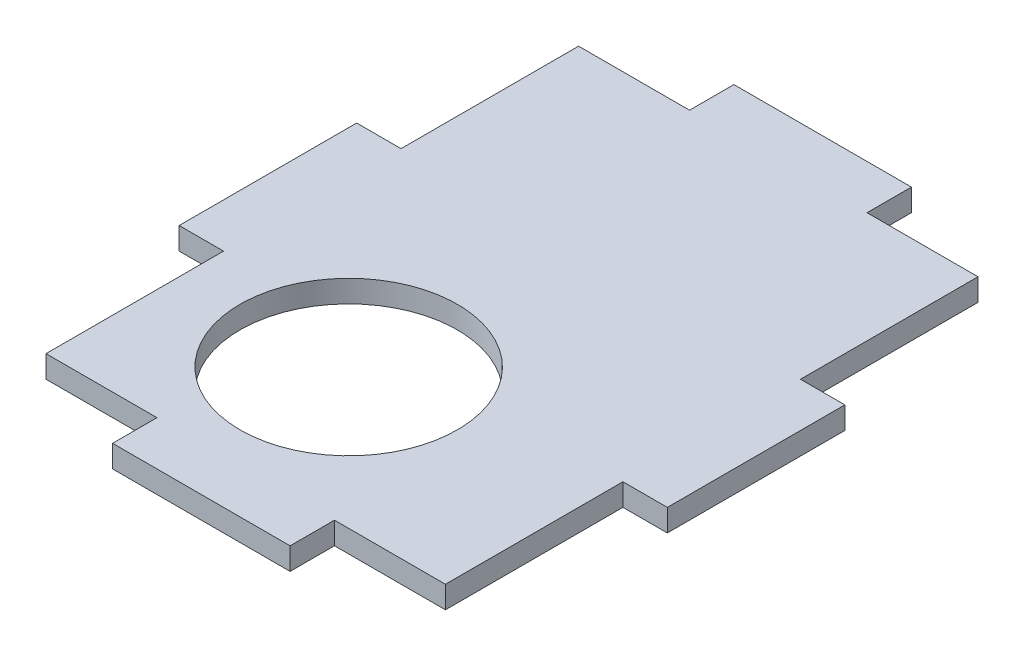
SolidWorks part; units mm, degrees
ref_plane "Front Plane" through (0, 0, 0) normal (0, 0, 1) x (1, 0, 0)
ref_plane "Top Plane" through (0, 0, 0) normal (0, 1, 0) x (1, 0, 0)
ref_plane "Right Plane" through (0, 0, 0) normal (1, 0, 0) x (0, 0, -1)
sketch "Sketch1" plane through (0, 0, 0) normal (0, 1, 0) x (1, 0, 0)
  line L1 (0, 0) -> (90, 0)
  line L2 (0, 0) -> (0, 120)
  line L3 (0, 120) -> (90, 120)
  line L4 (90, 0) -> (90, 120)
  line L5 (0, 80) -> (-10, 80)
  line L6 (0, 80) -> (0, 40)
  line L7 (0, 40) -> (-10, 40)
  line L8 (-10, 80) -> (-10, 40)
  line L9 (25, 120) -> (65, 120)
  line L10 (25, 120) -> (25, 130)
  line L11 (25, 130) -> (65, 130)
  line L12 (65, 120) -> (65, 130)
  line L13 (90, 80) -> (100, 80)
  line L14 (90, 80) -> (90, 40)
  line L15 (90, 40) -> (100, 40)
  line L16 (100, 80) -> (100, 40)
  line L17 (65, 0) -> (25, 0)
  line L18 (65, 0) -> (65, -10)
  line L19 (65, -10) -> (25, -10)
  line L20 (25, 0) -> (25, -10)
  circle A0 centre (36.72, 31.48) radius 24.5
  dimension "D17" = 49
  dimension "D1" = 90
  dimension "D2" = 120
  dimension "D3" = 10
  dimension "D4" = 10
  dimension "D5" = 10
  dimension "D6" = 10
  dimension "D7" = 40
  dimension "D8" = 40
  dimension "D9" = 40
  dimension "D10" = 40
  dimension "D11" = 40
  dimension "D12" = 25
  dimension "D13" = 40
  dimension "D14" = 25
  dimension "D15" = 36.72
  dimension "D16" = 31.48
extrude "Boss-Extrude1" add sketch "Sketch1" along normal blind 5 contours L1 L4 L3 L2 | L5 L8 L7 L2 | L16 L13 L4 L15 | L1 L20 L19 L18 | L11 L12 L9 L10
